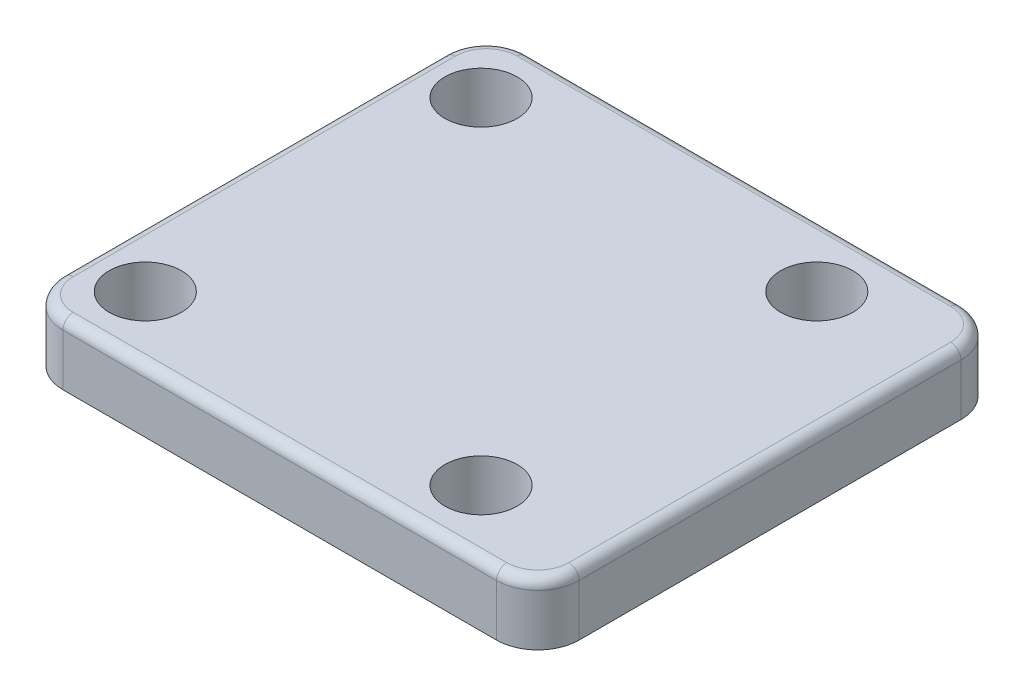
SolidWorks part; units mm, degrees
ref_plane "Front Plane" through (0, 0, 0) normal (0, 0, 1) x (1, 0, 0)
ref_plane "Top Plane" through (0, 0, 0) normal (0, 1, 0) x (1, 0, 0)
ref_plane "Right Plane" through (0, 0, 0) normal (1, 0, 0) x (0, 0, -1)
sketch "Sketch2" plane through (0, 0, 0) normal (0, 1, 0) x (1, 0, 0)
  line L1 (-18, 22.5) -> (24, 22.5)
  line L2 (-22, 18.5) -> (-22, -18.5)
  line L3 (-18, -22.5) -> (24, -22.5)
  line L4 (28, 18.5) -> (28, -18.5)
  arc A0 (24, 22.5) -> (28, 18.5) centre (24, 18.5) cw
  arc A1 (-22, -18.5) -> (-18, -22.5) centre (-18, -18.5) ccw
  arc A2 (24, -22.5) -> (28, -18.5) centre (24, -18.5) ccw
  arc A3 (-18, 22.5) -> (-22, 18.5) centre (-18, 18.5) ccw
  point P9 (-22, -22.5)
  point P12 (28, -22.5)
  point P15 (-22, 22.5)
  dimension "D5" = 4
  dimension "D1" = 45
  dimension "D2" = 50
  dimension "D3" = 22
  dimension "D4" = 22.5
extrude "Boss-Extrude1" add sketch "Sketch2" along normal blind 6
sketch "Sketch3" plane through (0, 0, 0) normal (0, -1, 0) x (1, 0, 0)
  circle A0 centre (0, 0) radius 16
  dimension "D1" = 32
extrude "Boss-Extrude2" add sketch "Sketch3" along normal blind 2
chamfer "Chamfer1" distance 1 angle 45 1 edges at (0, -2, -16)
sketch "Sketch4" plane through (0, 6, 0) normal (0, 1, 0) x (1, 0, 0)
  line L0 (0, 0) -> (16.2635, 16.2635) construction
  line L1 (0, 0) -> (36.3051, 0) construction
  circle A0 centre (0, 0) radius 23 construction
  circle A1 centre (16.2635, 16.2635) radius 3.5
  circle A2 centre (16.2635, -16.2635) radius 3.5
  circle A3 centre (-16.2635, -16.2635) radius 3.5
  circle A4 centre (-16.2635, 16.2635) radius 3.5
  point P15 (0, 0)
  dimension "D1" = 46
  dimension "D2" = 7
  dimension "D3" = 45
  dimension "D4" = 4
extrude "Cut-Extrude1" cut sketch "Sketch4" against normal through all
fillet "Fillet1" radius 1 8 edges at (-20.8284, 6, 21.3284) (-22, 6, 0) (-20.8284, 6, -21.3284) (3, 6, -22.5) (26.8284, 6, -21.3284) (28, 6, 0) (26.8284, 6, 21.3284) (3, 6, 22.5)
